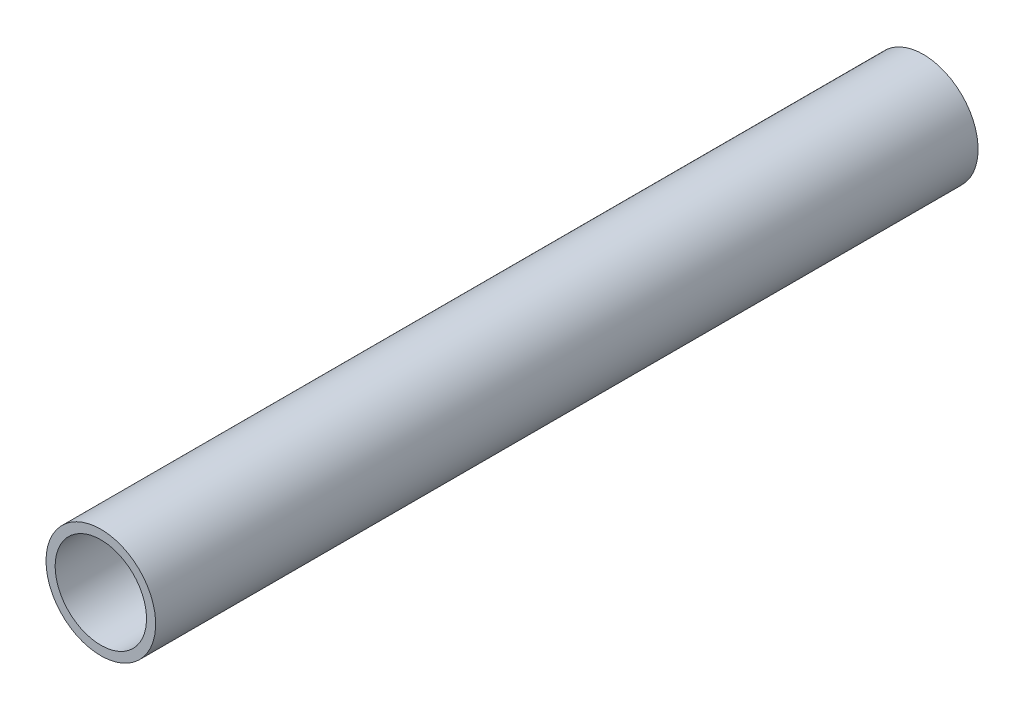
SolidWorks part; units mm, degrees
material "1023 Tôle d'acier au carbone (SS)"
ref_plane "Plan de face" through (0, 0, 0) normal (0, 0, 1) x (1, 0, 0)
ref_plane "Plan de dessus" through (0, 0, 0) normal (0, 1, 0) x (1, 0, 0)
ref_plane "Plan de droite" through (0, 0, 0) normal (1, 0, 0) x (0, 0, -1)
sketch "Esquisse1" plane through (0, 0, 0) normal (0, 0, 1) x (1, 0, 0)
  circle A0 centre (0, 0) radius 6
  circle A1 centre (0, 0) radius 5
  dimension "D1" = 12
  dimension "D2" = 1
extrude "Boss.-Extru.1" add sketch "Esquisse1" along normal blind 90
